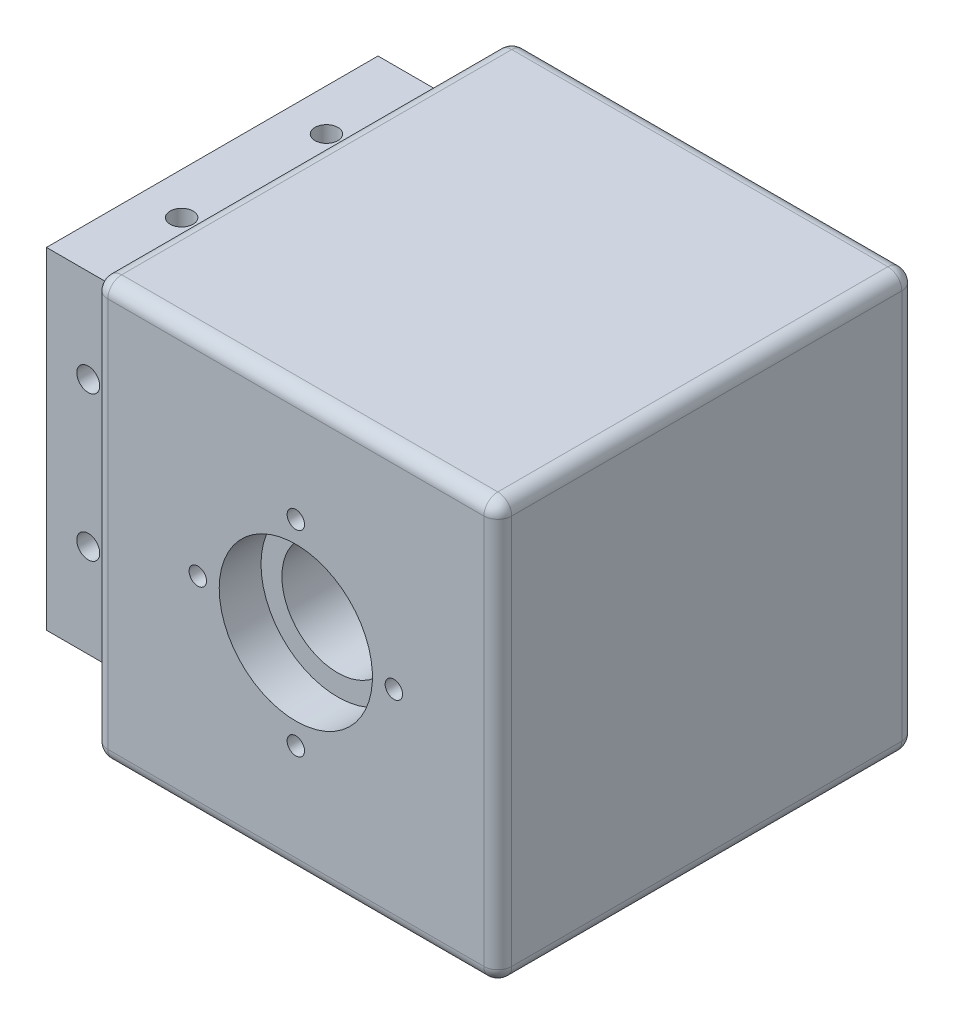
SolidWorks part; units mm, degrees
ref_plane "Front Plane" through (0, 0, 0) normal (0, 0, 1) x (1, 0, 0)
ref_plane "Top Plane" through (0, 0, 0) normal (0, 1, 0) x (1, 0, 0)
ref_plane "Right Plane" through (0, 0, 0) normal (1, 0, 0) x (0, 0, -1)
sketch "Sketch1" plane through (0, 0, 0) normal (0, 0, 1) x (1, 0, 0)
  line L1 (-30, -30) -> (30, -30)
  line L2 (-30, -30) -> (-30, 30)
  line L3 (-30, 30) -> (30, 30)
  line L4 (30, -30) -> (30, 30)
  line L5 (-30, -30) -> (30, 30) construction
  line L6 (-30, 30) -> (30, -30) construction
  point P0 (0, 0)
  dimension "D1" = 60
  dimension "60" = 60
extrude "Boss-Extrude1" add sketch "Sketch1" along normal blind 80
sketch "Sketch3" plane through (0, 0, 0) normal (0, 0, -1) x (-1, 0, 0)
  line L0 (-30, -30) -> (-30, 30) construction
  line L1 (-30, 30) -> (30, 30) construction
  circle A1 centre (-12, 0) radius 11
  point P7 (-12, 0)
  point P8 (-12, 0)
  dimension "D1" = 22
  dimension "D2" = 18
  dimension "D3" = 30
extrude "Cut-Extrude2" cut sketch "Sketch3" against normal blind 16 and the other way through all
sketch "Sketch4" plane through (-30, 0, 0) normal (-1, 0, 0) x (0, 0, 1)
  line L0 (0, 30) -> (0, -30) construction
  line L1 (63.8, -23.8) -> (16.2, -23.8)
  line L2 (63.8, -23.8) -> (63.8, 23.8)
  line L3 (63.8, 23.8) -> (16.2, 23.8)
  line L4 (16.2, -23.8) -> (16.2, 23.8)
  line L5 (63.8, -23.8) -> (16.2, 23.8) construction
  line L6 (63.8, 23.8) -> (16.2, -23.8) construction
  point P0 (40, 0)
  point P7 (0, 0)
  dimension "D1" = 47.6
  dimension "D2" = 47.6
  dimension "D3" = 40
  dimension "D4" = 30
extrude "Cut-Extrude5" cut sketch "Sketch4" against normal blind 13 flip side to cut
sketch "Sketch7" plane through (-30, 0, 0) normal (-1, 0, 0) x (0, 0, 1)
  point P0 (40, 0)
  dimension "D1" = 23.8
sketch "Sketch8" plane through (0, 0, 0) normal (0, 1, 0) x (1, 0, 0)
  line L0 (-30, -40) -> (42.1546, -40) construction
ref_plane "Plane1" through (12, 0, 0) normal (1, 0, 0) x (0, 0, -1)
sketch "Sketch10" plane through (12, 0, 0) normal (1, 0, 0) x (0, 0, -1)
  line L0 (0, 0) -> (-85.9366, 0) construction
ref_plane "Plane2" through (0, 0, 40) normal (0, 0, -1) x (-1, 0, 0)
ref_plane "Plane3" through (0, 0, 40) normal (0, 0, 1) x (1, 0, 0)
sketch "Sketch17" plane through (0, 0, 0) normal (0, 1, 0) x (1, 0, 0)
  line L0 (-30, -40) -> (38.2918, -40) construction
  line L1 (-30, -16.2) -> (-30, -63.8) construction
  line L2 (-33, -40) -> (33, -40) construction
hole_wizard "M4 Tapped Hole2" positions "Sketch18" profile "Sketch19" tap size "M4" standard "ISO"
sketch "Sketch18" plane through (0, -23.8, 0) normal (0, -1, 0) x (-1, 0, 0)
  point P0 (24, -29.6)
  point P2 (24, -50.4)
  dimension "D1" = 13.4
  dimension "D2" = 13.4
  dimension "D3" = 7
  dimension "D4" = 7
sketch "Sketch19" plane through (-24, -23.8, 29.6) normal (1, 0, 0) x (0, 0, -1)
  line L0 (0, 0) -> (0, 12.4914)
  line L1 (0, 12.4914) -> (1.65, 11.5)
  line L2 (1.65, 11.5) -> (1.65, 0)
  line L5 (1.65, 0) -> (0, 0)
  line L10 (0, 12.4914) -> (-1.65, 11.5) construction
  line L11 (0, -6.35) -> (0, 107.95) construction
  dimension "Tap Drill Dia." = 3.3
  dimension "Tap Drill Depth" = 11.5
  dimension "Drill Angle" = 118
cosmetic thread "Hole Thread3" parameters "D1"=8, "D2"=4
cosmetic thread "Hole Thread4" parameters "D1"=8, "D2"=4
pattern_circular "CirPattern2" count 4 every 90 about axis through (-30, 0, 40) along (1, 0, 0) of "M4 Tapped Hole2"
sketch "Sketch21" plane through (0, 0, 16) normal (0, 0, -1) x (-1, 0, 0)
  circle A6 centre (-12, 0) radius 8
  dimension "D1" = 16
mirror "Mirror2" about plane through (0, 0, 40) normal (0, 0, -1) of "Cut-Extrude2"
hole_wizard "M3 Tapped Hole1" positions "Sketch22" profile "Sketch23" tap size "M3" standard "ISO"
sketch "Sketch22" plane through (0, 0, 0) normal (0, 0, -1) x (-1, 0, 0)
  point P0 (-26.0731, 0)
cosmetic thread "Hole Thread5" parameters "D1"=18, "D2"=3
sketch "Sketch23" plane through (26.0731, 0, 0) normal (1, 0, 0) x (0, 1, 0)
  line L0 (0, 0) -> (0, 25.7511)
  line L1 (0, 25.7511) -> (1.25, 25)
  line L2 (1.25, 25) -> (1.25, 0)
  line L5 (1.25, 0) -> (0, 0)
  line L10 (0, 25.7511) -> (-1.25, 25) construction
  line L11 (0, -6.35) -> (0, 107.95) construction
  dimension "Tap Drill Dia." = 2.5
  dimension "Tap Drill Depth" = 25
  dimension "Drill Angle" = 118
pattern_circular "CirPattern4" count 4 every 90 about axis through (12, 0, 0) along (0, 0, 1) of "M3 Tapped Hole1"
mirror "Mirror3" about plane through (0, 0, 40) normal (0, 0, -1) of "CirPattern4", "M3 Tapped Hole1"
extrude "Cut-Extrude6" cut sketch "Sketch21" against normal through all contours A6
sketch "Sketch24" plane through (30, 0, 0) normal (1, 0, 0) x (0, 0, -1)
  line L0 (-80, -30) -> (0, -30) construction
  line L1 (0, 30) -> (-10, 30)
  line L2 (0, 30) -> (0, -30)
  line L3 (0, -30) -> (-10, -30)
  line L4 (-10, 30) -> (-10, -30)
  line L6 (-80, 30) -> (-70, 30)
  line L7 (-80, 30) -> (-80, -30)
  line L8 (-80, -30) -> (-70, -30)
  line L9 (-70, 30) -> (-70, -30)
  dimension "D1" = 10
  dimension "D2" = 10
extrude "Cut-Extrude7" cut sketch "Sketch24" against normal blind 53
sketch "Sketch25" plane through (30, 0, 0) normal (1, 0, 0) x (0, 0, -1)
  line L1 (-10, 30) -> (-70, 30)
  line L2 (-10, 30) -> (-10, -30)
  line L3 (-10, -30) -> (-70, -30)
  line L4 (-70, 30) -> (-70, -30)
extrude "Boss-Extrude2" add sketch "Sketch25" along normal blind 11
fillet "Fillet1" radius 2 12 edges at (41, -30, 40) (41, 0, 70) (41, 30, 40) (41, 0, 10) (12, 30, 70) (12, -30, 70) (12, -30, 10) (12, 30, 10) (-17, 0, 10) (-17, 30, 40) (-17, 0, 70) (-17, -30, 40)
